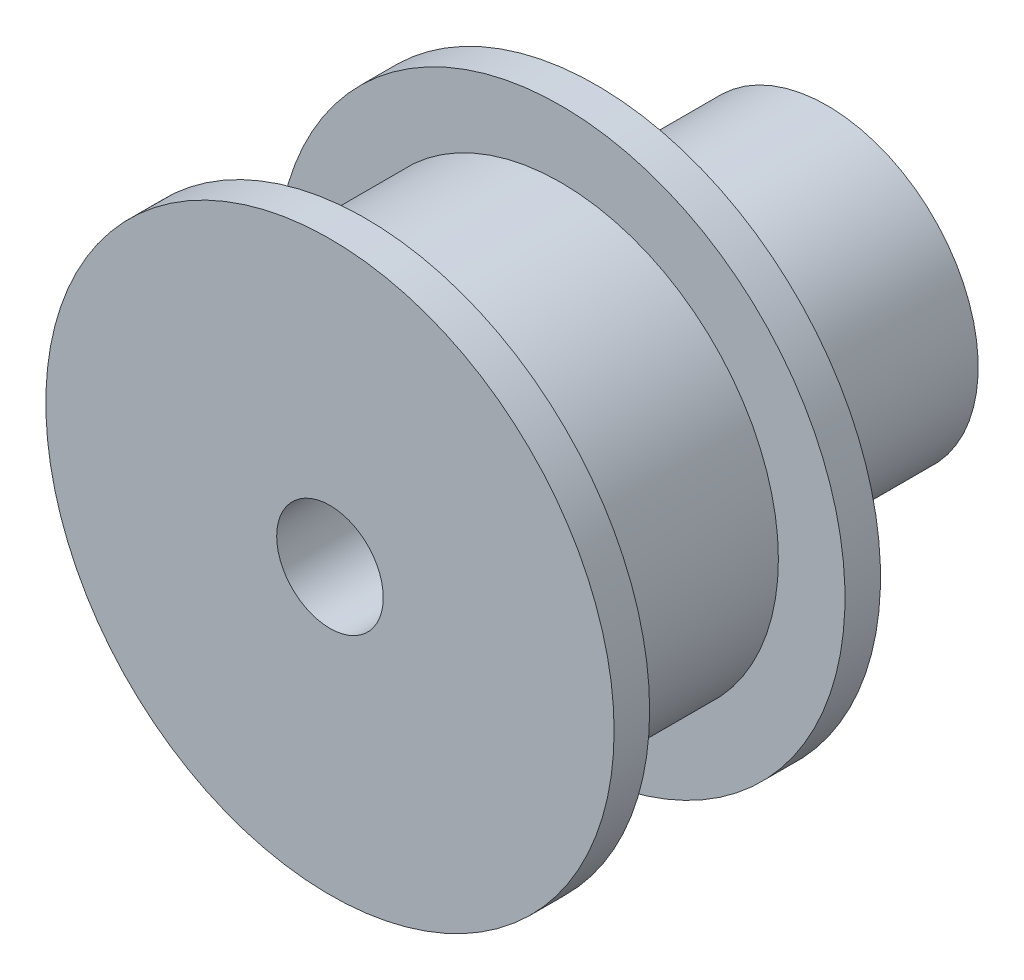
SolidWorks part; units mm, degrees
ref_plane "Front Plane" through (0, 0, 0) normal (0, 0, 1) x (1, 0, 0)
ref_plane "Top Plane" through (0, 0, 0) normal (0, 1, 0) x (1, 0, 0)
ref_plane "Right Plane" through (0, 0, 0) normal (1, 0, 0) x (0, 0, -1)
sketch "Sketch1" plane through (0, 0, 0) normal (0, 0, 1) x (1, 0, 0)
  circle A0 centre (0, 0) radius 12.25
  dimension "D1" = 24.5
extrude "Boss-Extrude1" add sketch "Sketch1" along normal blind 11
sketch "Sketch2" plane through (0, 0, 0) normal (0, 0, -1) x (-1, 0, 0)
  circle A2 centre (0, 0) radius 16
  dimension "D1" = 32
extrude "Boss-Extrude2" add sketch "Sketch2" along normal blind 2
sketch "Sketch3" plane through (0, 0, 11) normal (0, 0, 1) x (1, 0, 0)
  circle A0 centre (0, 0) radius 16
  dimension "D1" = 32
sketch "Sketch4" plane through (0, 0, -2) normal (0, 0, -1) x (-1, 0, 0)
  circle A0 centre (0, 0) radius 10
  dimension "D1" = 20
extrude "Boss-Extrude4" add sketch "Sketch4" along normal blind 1
sketch "Sketch5" plane through (0, 0, -3) normal (0, 0, -1) x (-1, 0, 0)
  circle A0 centre (0, 0) radius 8.5
  dimension "D1" = 17
extrude "Boss-Extrude5" add sketch "Sketch5" along normal blind 12
sketch "Sketch6" plane through (0, 0, -15) normal (0, 0, -1) x (-1, 0, 0)
  circle A0 centre (0, 0) radius 3
  dimension "D1" = 6
extrude "Cut-Extrude1" cut sketch "Sketch6" against normal blind 100
chamfer "Chamfer1" distance 1 angle 45 1 edges at (-3, 0, -15)
extrude "Boss-Extrude6" add sketch "Sketch3" along normal blind 2
sketch "Sketch7" plane through (0, 0, 13) normal (0, 0, 1) x (1, 0, 0)
  circle A0 centre (0, 0) radius 3
  dimension "D1" = 6
extrude "Cut-Extrude2" cut sketch "Sketch7" against normal blind 10
